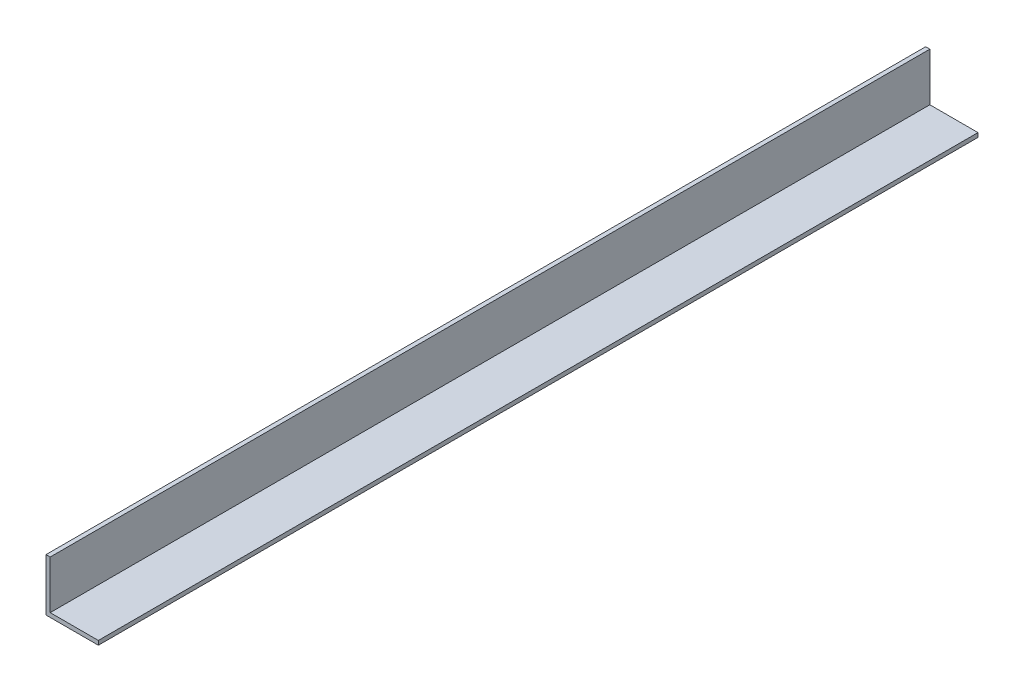
SolidWorks part; units mm, degrees
ref_plane "Front Plane" through (0, 0, 0) normal (0, 0, 1) x (1, 0, 0)
ref_plane "Top Plane" through (0, 0, 0) normal (0, 1, 0) x (1, 0, 0)
ref_plane "Right Plane" through (0, 0, 0) normal (1, 0, 0) x (0, 0, -1)
sketch "Sketch1" plane through (0, 0, 0) normal (0, 0, 1) x (1, 0, 0)
  line L0 (-36.6131, 18.1238) -> (-36.6131, -27.8762)
  line L1 (-36.6131, -27.8762) -> (9.3869, -27.8762)
  line L2 (9.3869, -27.8762) -> (9.3869, -31.8762)
  line L3 (9.3869, -31.8762) -> (-40.6131, -31.8762)
  line L4 (-40.6131, -31.8762) -> (-40.6131, 18.1238)
  line L5 (-40.6131, 18.1238) -> (-36.6131, 18.1238)
  dimension "D1" = 50
  dimension "D2" = 4
extrude "Boss-Extrude1" add sketch "Sketch1" along normal blind 840
